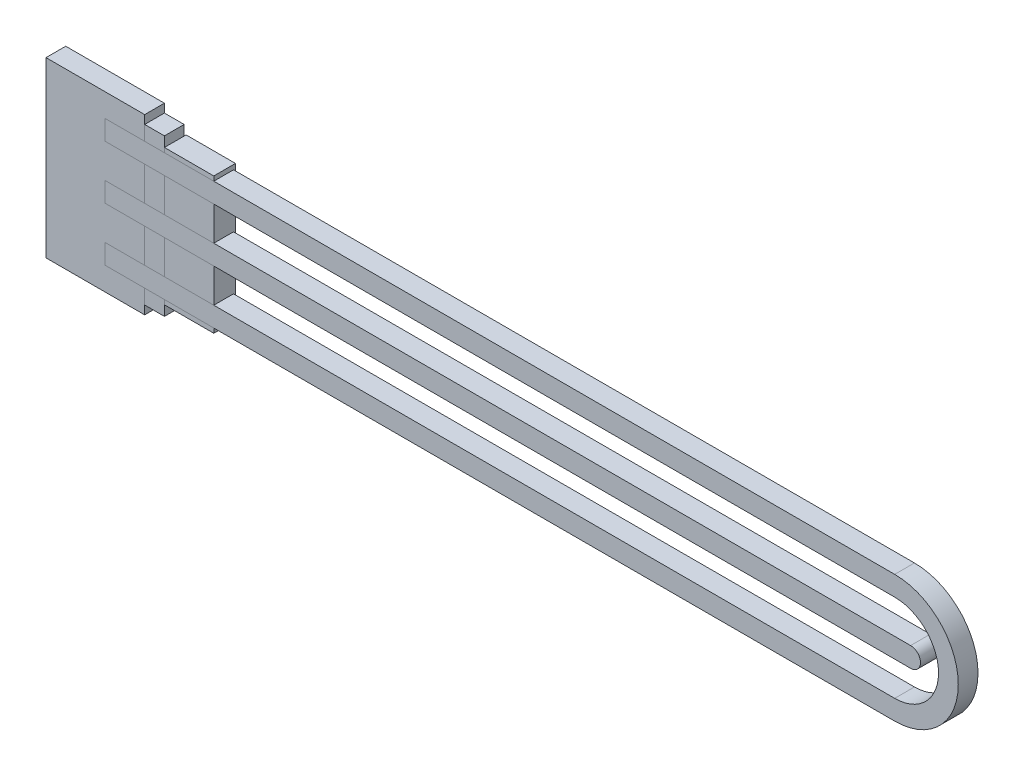
SolidWorks part; units mm, degrees
ref_plane "Alzado" through (0, 0, 0) normal (0, 0, 1) x (1, 0, 0)
ref_plane "Planta" through (0, 0, 0) normal (0, 1, 0) x (1, 0, 0)
ref_plane "Vista lateral" through (0, 0, 0) normal (1, 0, 0) x (0, 0, -1)
sketch "Sketch1" plane through (0, 0, 0) normal (0, 0, 1) x (1, 0, 0)
  line L0 (0, 0) -> (400, 0)
  line L1 (400, -64.4097) -> (0, -64.4097)
  line L2 (0, -10) -> (400, -10)
  line L3 (400, -54.4097) -> (0, -54.4097)
  line L4 (0, -10) -> (0, 0)
  line L5 (0, -54.4097) -> (0, -64.4097)
  line L6 (432.2048, -32.2048) -> (0, -32.2048) construction
  line L7 (0, -27.2048) -> (408.0642, -27.2048)
  line L8 (0, -27.2048) -> (0, -37.2048)
  line L9 (0, -37.2048) -> (408.0642, -37.2048)
  arc A0 (400, 0) -> (400, -64.4097) centre (400, -32.2048) cw
  arc A1 (400, -10) -> (400, -54.4097) centre (400, -32.2048) cw
  arc A4 (408.0642, -27.2048) -> (408.0642, -37.2048) centre (408.0642, -32.2048) cw
  dimension "D1" = 32.2048
  dimension "D3" = 10
  dimension "D2" = 400
  dimension "D4" = 5
extrude "Boss-Extrude1" add sketch "Sketch1" along normal blind 10
sketch "Sketch2" plane through (0, 0, 0) normal (-1, 0, 0) x (0, 0, 1)
  line L0 (5, 0) -> (5, -10) construction
  line L1 (10, 0) -> (0, 0) construction
  line L2 (10, -10) -> (0, -10) construction
  circle A0 centre (5, -4.907) radius 3
  dimension "D1" = 6
extrude "Boss-Extrude2" add sketch "Sketch2" along normal blind 15 separate body
sketch "Sketch3" plane through (0, 0, 0) normal (-1, 0, 0) x (0, 0, 1)
  line L0 (5, -54.4097) -> (5, -64.4097) construction
  line L1 (10, -54.4097) -> (0, -54.4097) construction
  line L2 (10, -64.4097) -> (0, -64.4097) construction
  circle A0 centre (5, -59.4097) radius 3
  dimension "D1" = 6
extrude "Boss-Extrude3" add sketch "Sketch3" along normal blind 15 separate body
sketch "Sketch4" plane through (0, 0, 0) normal (0, 0, 1) x (1, 0, 0)
  line L0 (0, -32.2048) -> (68.9796, -32.2048) construction
  line L1 (30, 2.3126) -> (55, 2.3126)
  line L2 (30, 2.3126) -> (30, -66.7223)
  line L3 (30, -66.7223) -> (55, -66.7223)
  line L4 (55, 2.3126) -> (55, -66.7223)
  line L5 (0, -27.2048) -> (0, -37.2048) construction
  dimension "D1" = 25
extrude "Boss-Extrude4" add sketch "Sketch4" along normal up to surface (10 mm away) and the other way blind 1 separate body up to face at (205.2821, -32.2048, 10)
sketch "Sketch5" plane through (0, 0, 0) normal (0, 0, 1) x (1, 0, 0)
  line L0 (30, -66.7223) -> (30, 2.3126) construction
  line L1 (30, 7.4097) -> (20, 7.4097)
  line L2 (30, 7.4097) -> (30, -71.8194)
  line L3 (30, -71.8194) -> (20, -71.8194)
  line L4 (20, 7.4097) -> (20, -71.8194)
  line L5 (0, -32.2048) -> (76.9498, -32.2048) construction
  line L6 (0, -27.2048) -> (0, -37.2048) construction
  dimension "D1" = 10
extrude "Boss-Extrude6" add sketch "Sketch5" along normal up to surface (10 mm away) separate body contours L4 L5 L2 L1 | L5 L4 L3 L2 up to face at (205.2821, -32.2048, 10)
sketch "Sketch6" plane through (0, 0, 0) normal (0, 0, 1) x (1, 0, 0)
  line L0 (20, -71.8194) -> (20, 7.4097) construction
  line L1 (20, 11.7376) -> (-30, 11.7376)
  line L2 (20, 11.7376) -> (20, -76.1473)
  line L3 (20, -76.1473) -> (-30, -76.1473)
  line L4 (-30, 11.7376) -> (-30, -76.1473)
  line L5 (0, -32.2048) -> (63.4262, -32.2048) construction
  line L6 (0, -27.2048) -> (0, -37.2048) construction
  dimension "D1" = 50
extrude "Boss-Extrude7" add sketch "Sketch6" along normal up to surface (10 mm away) separate body up to face at (205.2821, -32.2048, 10)
